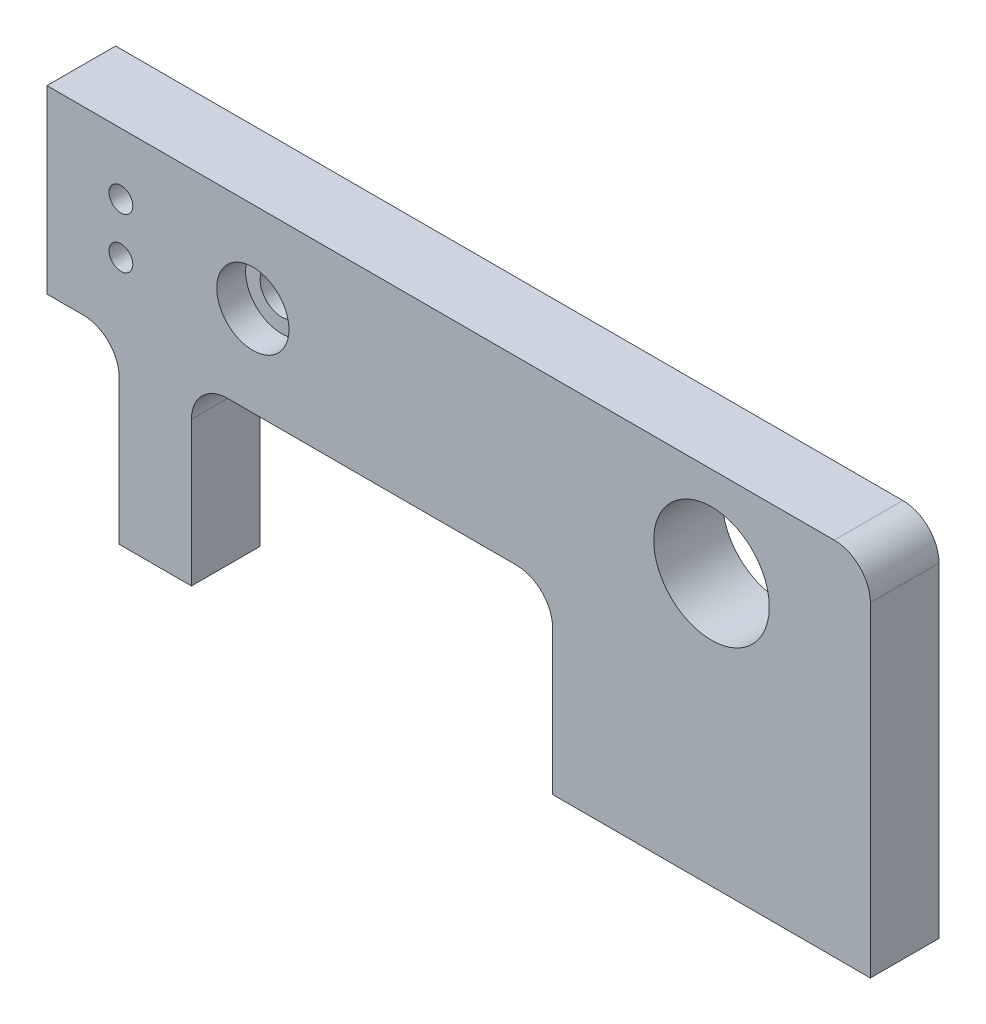
SolidWorks part; units mm, degrees
material "AISI 1045 Steel, cold drawn"
ref_plane "Front Plane" through (0, 0, 0) normal (0, 0, 1) x (1, 0, 0)
ref_plane "Top Plane" through (0, 0, 0) normal (0, 1, 0) x (1, 0, 0)
ref_plane "Right Plane" through (0, 0, 0) normal (1, 0, 0) x (0, 0, -1)
sketch "Sketch1" plane through (0, 0, 0) normal (0, 0, 1) x (1, 0, 0)
  line L1 (-57, -25) -> (57, -25)
  line L2 (-57, -25) -> (-57, 25)
  line L3 (-57, 25) -> (57, 25)
  line L4 (57, -25) -> (57, 25)
  line L5 (-57, -25) -> (57, 25) construction
  line L6 (-57, 25) -> (57, -25) construction
  point P0 (0, 0)
  dimension "D1" = 114
  dimension "D2" = 50
extrude "Boss-Extrude1" add sketch "Sketch1" along normal mid plane 9.5
sketch "Sketch2" plane through (0, 0, 4.75) normal (0, 0, 1) x (1, 0, 0)
  line L0 (-57, -25) -> (57, -25) construction
  line L2 (-37, -25) -> (-37, -5)
  line L3 (-32, 0) -> (8, 0)
  line L4 (13, -25) -> (13, -5)
  line L5 (57, -25) -> (57, 25) construction
  line L9 (-57, -25) -> (57, -25)
  line L10 (-37, -25) -> (13, -25)
  line L12 (-57, 0) -> (-52, 0)
  line L13 (-47, -25) -> (-47, -5)
  line L14 (57, 25) -> (-57, 25) construction
  line L17 (-37, -25) -> (57, -25)
  line L19 (-57, -25) -> (57, -25)
  line L20 (-57, 25) -> (-57, -25)
  line L21 (-57, -25) -> (-47, -25)
  line L22 (-57, 0) -> (-57, -25)
  arc A0 (-32, 0) -> (-37, -5) centre (-32, -5) ccw
  arc A1 (8, 0) -> (13, -5) centre (8, -5) cw
  arc A2 (-52, 0) -> (-47, -5) centre (-52, -5) cw
  circle A3 centre (35, 12.5) radius 8
  point P0 (-16.216, -25)
  point P15 (13, 0)
  point P16 (-57, -25)
  point P20 (-47, 0)
  line M16 (-57, 25) -> (-57, -25)
  line M17 (-57, -25) -> (57, -25)
  dimension "D5" = 5
  dimension "D9" = 5
  dimension "D12" = 16
  dimension "D2" = 44
  dimension "D3" = 50
  dimension "D4" = 25
  dimension "D7" = 10
  dimension "D8" = 25
  dimension "D10" = 22
  dimension "D11" = 12.5
  dimension "D1" = 0
  dimension "D6" = 0
extrude "Cut-Extrude1" cut sketch "Sketch2" against normal through all contours A1 L3 A0 L2 L4 M17 | A2 L12 L13 M16 M17 | A3
fillet "Fillet1" radius 5 1 edges at (57, 25, 0)
sketch "Sketch3" plane through (0, 0, 4.75) normal (0, 0, 1) x (1, 0, 0)
  line L0 (57, -25) -> (57, 20) construction
  line L1 (52, 25) -> (-57, 25) construction
  circle A0 centre (-28.5, 12.5) radius 5
  dimension "D1" = 85.5
  dimension "D2" = 12.5
extrude "Cut-Extrude2" cut sketch "Sketch3" against normal blind 4
sketch "Sketch4" plane through (0, 0, 0.75) normal (0, 0, 1) x (1, 0, 0)
  circle A0 centre (-28.5, 12.5) radius 3
extrude "Cut-Extrude3" cut sketch "Sketch4" against normal through all
hole_wizard "M4 Tapped Hole1" positions "Sketch5" profile "Sketch6" tap size "M4" standard "ISO" end condition through all
sketch "Sketch5" plane through (0, 0, 4.75) normal (0, 0, 1) x (1, 0, 0)
  line L0 (57, -25) -> (57, 20) construction
  line L1 (52, 25) -> (-57, 25) construction
  point P0 (-46.77, 9.5)
  point P2 (-46.77, 16.5)
  point P7 (0, 0)
  dimension "D1" = 103.77
  dimension "D2" = 7
  dimension "D3" = 8.5
sketch "Sketch6" plane through (-46.77, 9.5, 4.75) normal (1, 0, 0) x (0, -1, 0)
  line L0 (0, 0) -> (0, 9.5)
  line L1 (0, 9.5) -> (1.65, 9.5)
  line L2 (1.65, 9.5) -> (1.65, 0)
  line L5 (1.65, 0) -> (0, 0)
  line L11 (0, -6.35) -> (0, 107.95) construction
  dimension "Thru Tap Drill Dia." = 3.3
  dimension "Thru Tap Drill Depth" = 9.5
cosmetic thread "Hole Thread1" parameters "D2"=4
cosmetic thread "Hole Thread2" parameters "D2"=4
hole_wizard "M4 Tapped Hole2" positions "Sketch7" profile "Sketch8" tap size "M4" standard "ISO"
sketch "Sketch7" plane through (0, -25, 0) normal (0, -1, 0) x (-1, 0, 0)
  line L0 (-57, -4.75) -> (-57, 4.75) construction
  point P0 (42, 0)
  point P2 (-21, 0)
  point P4 (-49, 0)
  point P7 (0, 0)
  dimension "D1" = 8
  dimension "D2" = 36
  dimension "D3" = 99
sketch "Sketch8" plane through (-42, -25, 0) normal (1, 0, 0) x (0, 0, -1)
  line L0 (0, 0) -> (0, 15.0914)
  line L1 (0, 15.0914) -> (1.65, 14.1)
  line L2 (1.65, 14.1) -> (1.65, 0)
  line L5 (1.65, 0) -> (0, 0)
  line L10 (0, 15.0914) -> (-1.65, 14.1) construction
  line L11 (0, -6.35) -> (0, 107.95) construction
  dimension "Tap Drill Dia." = 3.3
  dimension "Tap Drill Depth" = 14.1
  dimension "Drill Angle" = 118
cosmetic thread "Hole Thread3" parameters "D1"=12, "D2"=4
cosmetic thread "Hole Thread4" parameters "D1"=12, "D2"=4
cosmetic thread "Hole Thread5" parameters "D1"=12, "D2"=4
